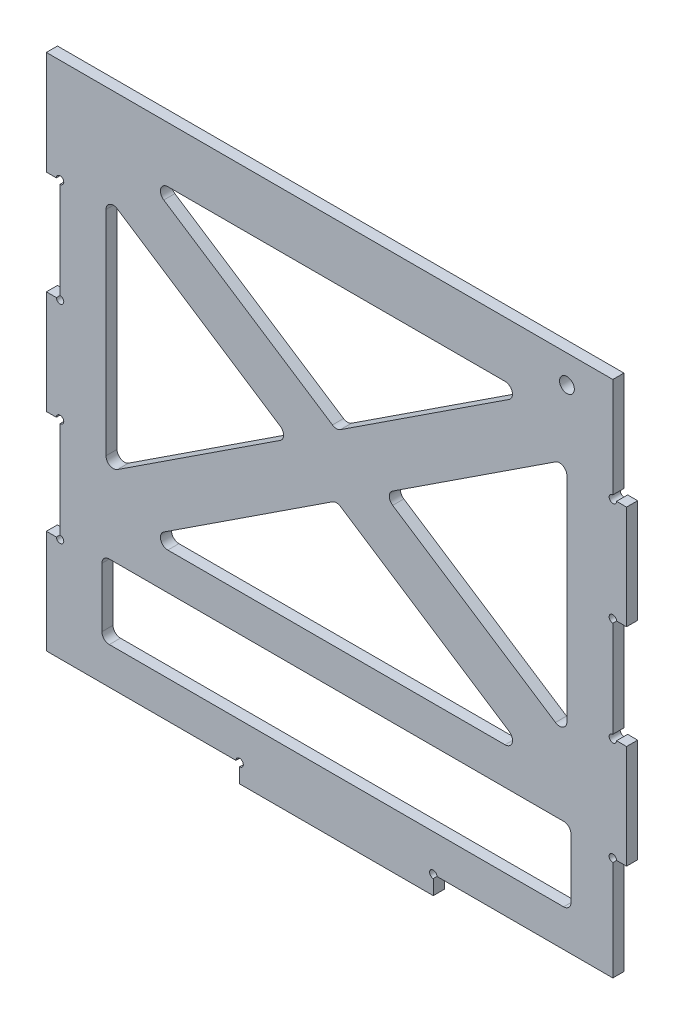
SolidWorks part; units mm, degrees
material "Alumina"
ref_plane "Front Plane" through (0, 0, 0) normal (0, 0, 1) x (1, 0, 0)
ref_plane "Top Plane" through (0, 0, 0) normal (0, 1, 0) x (1, 0, 0)
ref_plane "Right Plane" through (0, 0, 0) normal (1, 0, 0) x (0, 0, -1)
sketch "Sketch1" plane through (0, 0, 0) normal (0, 0, 1) x (1, 0, 0)
  line L1 (-78.35, -70) -> (78.35, -70)
  line L2 (-78.35, -70) -> (-78.35, 70)
  line L3 (-78.35, 70) -> (78.35, 70)
  line L4 (78.35, -70) -> (78.35, 70)
  line L5 (-78.35, -70) -> (78.35, 70) construction
  line L6 (-78.35, 70) -> (78.35, -70) construction
  point P0 (0, 0)
extrude "Boss-Extrude1" add sketch "Sketch1" along normal blind 3
sketch "Sketch2" plane through (0, 0, 3) normal (0, 0, 1) x (1, 0, 0)
  line L0 (-78.35, -70) -> (78.35, -70) construction
  line L1 (-63.35, -60) -> (63.35, -60)
  line L2 (-63.35, -60) -> (-63.35, -40)
  line L3 (-63.35, -40) -> (63.35, -40)
  line L4 (63.35, -60) -> (63.35, -40)
  line L5 (-63.35, -60) -> (63.35, -40) construction
  line L6 (-63.35, -40) -> (63.35, -60) construction
  line L7 (-78.35, 70) -> (-78.35, -70) construction
  line L8 (78.35, -70) -> (78.35, 70) construction
  line L9 (78.35, 70) -> (-78.35, 70) construction
  line L10 (-62.25, -30) -> (62.25, -30)
  line L11 (-62.25, -30) -> (-62.25, 55)
  line L12 (-62.25, 55) -> (62.25, 55)
  line L13 (62.25, -30) -> (62.25, 55)
  line L14 (-62.25, -30) -> (62.25, 55) construction
  line L15 (-62.25, 55) -> (62.25, -30) construction
  line L16 (-62.25, 45) -> (52.25, -30)
  line L17 (-52.25, 55) -> (62.25, -20)
  line L18 (52.25, 55) -> (-62.25, -20)
  line L19 (-52.25, -30) -> (62.25, 45)
  point P0 (0, -50)
  point P11 (0, 12.5)
  dimension "D1" = 10
  dimension "D2" = 15
  dimension "D3" = 15
  dimension "D4" = 15
  dimension "D5" = 10
  dimension "D6" = 10
  dimension "D7" = 10
  dimension "D8" = 10
  dimension "D9" = 10
extrude "Cut-Extrude1" cut sketch "Sketch2" against normal through all contours L1 L4 L3 L2 | L18 L16 L11 | L19 L10 L16 | L18 L12 L17 | L19 L17 L13
fillet "Fillet1" radius 2 16 edges at (52.25, -30, 1.5) (-62.25, -20, 1.5) (-52.25, 55, 1.5) (-52.25, -30, 1.5) (-62.25, 45, 1.5) (-63.35, -40, 1.5) (0, 4.2249, 1.5) (62.25, 45, 1.5) (63.35, -40, 1.5) (52.25, 55, 1.5) (-12.6333, 12.5, 1.5) (0, 20.7751, 1.5) (62.25, -20, 1.5) (63.35, -60, 1.5) (-63.35, -60, 1.5) (12.6333, 12.5, 1.5)
sketch "Sketch3" plane through (0, 0, 3) normal (0, 0, 1) x (1, 0, 0)
  line L0 (-78.35, 70) -> (-78.35, -70) construction
  line L1 (-78.35, 42) -> (-74.65, 42)
  line L2 (-78.35, 42) -> (-78.35, 14)
  line L3 (-78.35, 14) -> (-74.65, 14)
  line L4 (-74.65, 42) -> (-74.65, 14)
  line L5 (78.35, 70) -> (-78.35, 70) construction
  line L6 (78.35, -70) -> (78.35, 70) construction
  line L7 (-78.35, -42) -> (-74.65, -42)
  line L8 (-78.35, -42) -> (-78.35, -14)
  line L9 (-78.35, -14) -> (-74.65, -14)
  line L10 (-74.65, -42) -> (-74.65, -14)
  line L11 (78.35, 70) -> (74.65, 70)
  line L12 (78.35, 70) -> (78.35, 42)
  line L13 (78.35, 42) -> (74.65, 42)
  line L14 (74.65, 70) -> (74.65, 42)
  line L15 (78.35, 14) -> (74.65, 14)
  line L16 (78.35, 14) -> (78.35, -14)
  line L17 (78.35, -14) -> (74.65, -14)
  line L18 (74.65, 14) -> (74.65, -14)
  line L20 (78.35, -70) -> (74.65, -70)
  line L21 (78.35, -70) -> (78.35, -42)
  line L22 (78.35, -42) -> (74.65, -42)
  line L23 (74.65, -70) -> (74.65, -42)
  dimension "D1" = 28
  dimension "D2" = 28
extrude "Cut-Extrude2" cut sketch "Sketch3" against normal through all
sketch "Sketch4" plane through (0, 0, 3) normal (0, 0, 1) x (1, 0, 0)
  line L0 (-78.35, -70) -> (74.65, -70) construction
  line L1 (-26.15, -75) -> (26.15, -75)
  line L2 (-26.15, -75) -> (-26.15, -70)
  line L3 (-26.15, -70) -> (26.15, -70)
  line L4 (26.15, -75) -> (26.15, -70)
  line L5 (-26.15, -75) -> (26.15, -70) construction
  line L6 (-26.15, -70) -> (26.15, -75) construction
  point P0 (0, -72.5)
extrude "Boss-Extrude2" add sketch "Sketch4" against normal blind 3
sketch "Sketch5" plane through (0, 0, 3) normal (0, 0, 1) x (1, 0, 0)
  circle A0 centre (-74.65, 42) radius 1
  circle A1 centre (-74.65, 14) radius 1
  circle A2 centre (-74.65, -14) radius 1
  circle A3 centre (-74.65, -42) radius 1
  circle A4 centre (-26.15, -70) radius 1
  circle A5 centre (26.15, -70) radius 1
  circle A6 centre (74.65, -42) radius 1
  circle A7 centre (74.65, -14) radius 1
  circle A8 centre (74.65, 42) radius 1
  circle A9 centre (74.65, 14) radius 1
extrude "Cut-Extrude3" cut sketch "Sketch5" against normal through all
sketch "Sketch6" plane through (0, 0, 0) normal (0, 0, -1) x (-1, 0, 0)
  circle A0 centre (-62.25, 62.5) radius 2
extrude "Cut-Extrude4" cut sketch "Sketch6" against normal through all
